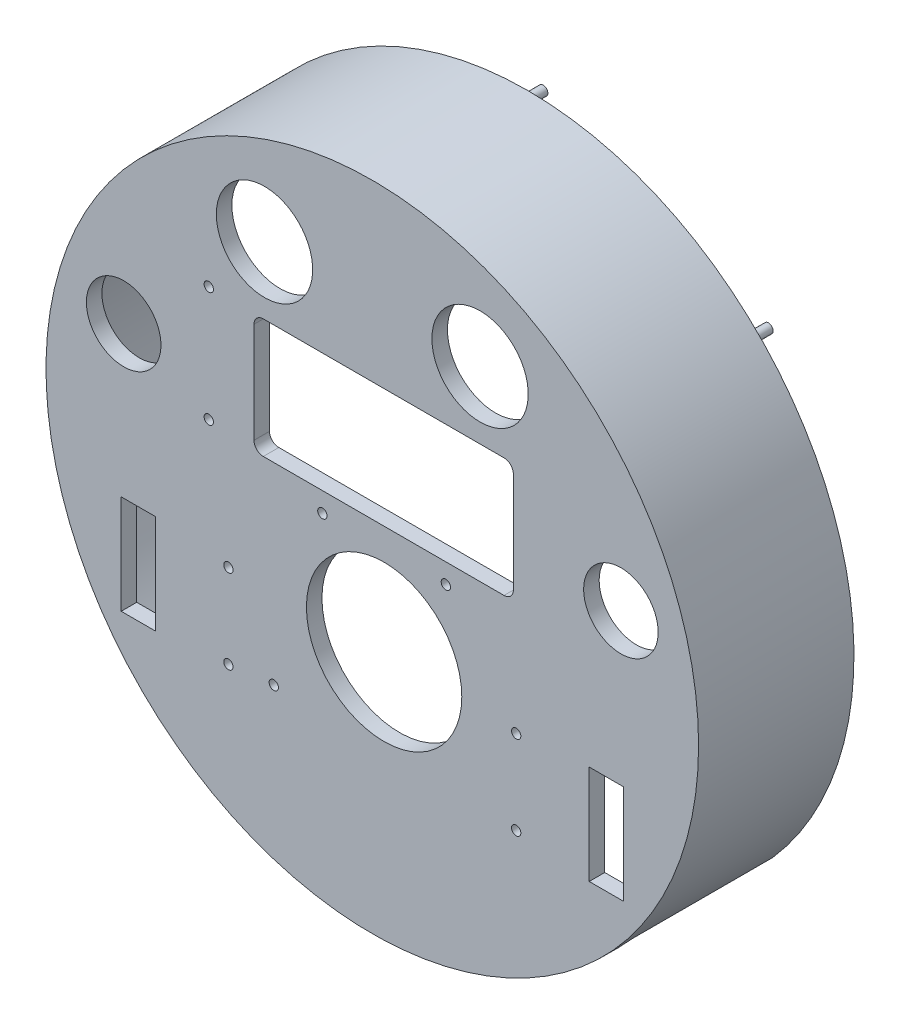
SolidWorks part; units mm, degrees
ref_plane "Plan de face" through (0, 0, 0) normal (0, 0, 1) x (1, 0, 0)
ref_plane "Plan de dessus" through (0, 0, 0) normal (0, 1, 0) x (1, 0, 0)
ref_plane "Plan de droite" through (0, 0, 0) normal (1, 0, 0) x (0, 0, -1)
sketch "Esquisse1" plane through (0, 0, 0) normal (0, 0, 1) x (1, 0, 0)
  circle A0 centre (0, 0) radius 105
  dimension "D1" = 210
extrude "Boss.-Extru.1" add sketch "Esquisse1" along normal blind 50
shell "Coque1" thickness 5
sketch3d "Esquisse3D1"
  line L0 (0, 0, 0) -> (0, 0, 42.8411) construction
  line L1 (0, -105, 0) -> (0, -105, 50) construction
  circle A3 centre (0, 0, 0) radius 105 construction
  circle A4 centre (0, 0, 50) radius 105 construction
  point P9 (0, 0, 105)
  point P12 (0, 0, 155)
sketch "Esquisse3" plane through (0, 0, 45) normal (0, 0, -1) x (-1, 0, 0)
  circle A0 centre (-3.8, -24.5576) radius 25
  circle A1 centre (-23.6695, 4.1345) radius 1.5
  circle A2 centre (16.0695, 4.1345) radius 1.5
  circle A3 centre (31.7, -51.5576) radius 1.5
extrude "Enlèv. mat.-Extru.1" cut sketch "Esquisse3" against normal blind 10
sketch "Esquisse5" plane through (0, 0, 45) normal (0, 0, -1) x (-1, 0, 0)
  line L1 (-42.3889, 10.4726) -> (35.0744, 10.4726)
  line L2 (-45.3889, 13.4726) -> (-45.3889, 45.8069)
  line L3 (-42.3889, 48.8069) -> (35.0744, 48.8069)
  line L4 (38.0744, 13.4726) -> (38.0744, 45.8069)
  arc A0 (35.0744, 48.8069) -> (38.0744, 45.8069) centre (35.0744, 45.8069) cw
  arc A1 (35.0744, 10.4726) -> (38.0744, 13.4726) centre (35.0744, 13.4726) ccw
  arc A2 (-42.3889, 10.4726) -> (-45.3889, 13.4726) centre (-42.3889, 13.4726) cw
  arc A3 (-45.3889, 45.8069) -> (-42.3889, 48.8069) centre (-42.3889, 45.8069) cw
  dimension "D1" = 3
extrude "Enlèv. mat.-Extru.2" cut sketch "Esquisse5" against normal through all
sketch "Esquisse6" plane through (0, 0, 0) normal (0, 0, -1) x (-1, 0, 0)
  line L0 (-78.8107, -69.3821) -> (78.8107, -69.3821)
  line L1 (78.5009, -69.3821) -> (-78.8107, -69.3821) construction
  circle A0 centre (0, 0) radius 105 construction
  arc A1 (-78.8107, -69.3821) -> (78.8107, -69.3821) centre (0, 0) ccw
extrude "Enlèv. mat.-Extru.3" cut sketch "Esquisse6" against normal blind 45
sketch "Esquisse7" plane through (0, 0, 45) normal (0, 0, -1) x (-1, 0, 0)
  circle A0 centre (52.6142, 48.9901) radius 1.5
  circle A1 centre (52.6142, 11.9901) radius 1.5
  circle A2 centre (46.3, -26.0576) radius 1.5
  circle A3 centre (46.3, -53.0576) radius 1.5
  circle A4 centre (-46.3, -26.0622) radius 1.5
  circle A5 centre (-46.3, -53.0622) radius 1.5
extrude "Enlèv. mat.-Extru.4" cut sketch "Esquisse7" against normal through all
sketch "Esquisse8" plane through (0, 0, 45) normal (0, 0, -1) x (-1, 0, 0)
  line L0 (0, 116.3573) -> (0, -138.2334) construction
  line L7 (-80.8, -55.5371) -> (-80.8, -23.6417)
  line L8 (-80.8, -23.6417) -> (-69.8, -23.6417)
  line L9 (-69.8, -55.5371) -> (-69.8, -23.6417)
  line L10 (-80.8, -55.5371) -> (-69.8, -55.5371)
  line L11 (80.8, -55.5371) -> (69.8, -55.5371)
  line L12 (69.8, -55.5371) -> (69.8, -23.6417)
  line L13 (80.8, -23.6417) -> (69.8, -23.6417)
  line L14 (80.8, -55.5371) -> (80.8, -23.6417)
extrude "Enlèv. mat.-Extru.5" cut sketch "Esquisse8" against normal blind 5
sketch "Esquisse9" plane through (0, 0, 45) normal (0, 0, -1) x (-1, 0, 0)
  circle A2 centre (34.6819, 70.4401) radius 15.5
  circle A3 centre (-34.6819, 70.4401) radius 15.5
extrude "Enlèv. mat.-Extru.7" cut sketch "Esquisse9" against normal through all
sketch "Esquisse10" plane through (-9.6819, 0.4401, 22) normal (0, 0, -1) x (-1, 0, 0)
  line L1 (-43.2214, 88.9656) -> (-42.9259, 93.8724)
  line L2 (-41.7241, 88.8754) -> (-44.7187, 89.0558) construction
  arc A0 (62.3329, -69.8221) -> (-81.6967, -69.8221) centre (-9.6819, -0.4401) ccw construction
sweep "Balayage1" add path "Esquisse10" circular profile diameter 3 parameters "D3"=3
sketch "Esquisse19" plane through (-5.54, 91.9764, 0) normal (-0.0601, 0.9982, 0) x (0.9982, 0.0601, 0)
  line L1 (38.8542, -23.5) -> (38.8542, -20.5)
  line L2 (38.8542, -23.5) -> (38.8542, -20.5)
  arc A1 (38.8542, -20.5) -> (38.8542, -23.5) centre (38.8542, -22) ccw
  arc A2 (38.8542, -20.5) -> (38.8542, -23.5) centre (38.8542, -22) ccw
  dimension "D1" = 0
extrude "Boss.-Extru.2" add sketch "Esquisse19" along normal blind 1
sketch "Esquisse20" plane through (-9.6819, 0.4401, 22) normal (0, 0, -1) x (-1, 0, 0)
  line L0 (-73.3113, 71.7436) -> (-78.4695, 72.1427)
  line L1 (-73.2211, 73.2409) -> (-73.4015, 70.2463) construction
  arc A0 (62.3329, -69.8221) -> (-81.6967, -69.8221) centre (-9.6819, -0.4401) ccw construction
sweep "Balayage2" add path "Esquisse20" circular profile diameter 3 parameters "D3"=3
sketch "Esquisse27" plane through (73.961, 5.7229, 0) normal (0.997, 0.0771, 0) x (0, 0, -1)
  line L1 (-20.5, 67.0598) -> (-23.5, 67.0598)
  line L2 (-20.5, 67.0598) -> (-23.5, 67.0598)
  arc A1 (-23.5, 67.0598) -> (-20.5, 67.0598) centre (-22, 67.0598) ccw
  arc A2 (-23.5, 67.0598) -> (-20.5, 67.0598) centre (-22, 67.0598) ccw
  dimension "D1" = 0
extrude "Boss.-Extru.3" add sketch "Esquisse27" along normal blind 2
mirror "Symétrie1" about plane through (0, 0, 0) normal (1, 0, 0) of "Balayage1", "Boss.-Extru.2", "Balayage2", "Boss.-Extru.3"
sketch "Esquisse30" plane through (0, 0, 0) normal (0, 0, -1) x (-1, 0, 0)
  line L2 (0, 145.1425) -> (0, 39.277) construction
  line L3 (0, 0) -> (-72.4784, 72.4784) construction
  line L4 (-78.8107, -69.3821) -> (-72.0148, -69.3821)
  line L5 (72.0148, -69.3821) -> (78.8107, -69.3821)
  line L6 (-78.8107, -69.3821) -> (-72.0148, -69.3821)
  line L7 (72.0148, -69.3821) -> (78.8107, -69.3821)
  arc A4 (78.8107, -69.3821) -> (-78.8107, -69.3821) centre (0, 0) ccw
  arc A5 (72.0148, -69.3821) -> (-72.0148, -69.3821) centre (0, 0) ccw
  circle A10 centre (0, 102.5) radius 1.5
  arc A11 (73.8152, -71.1166) -> (-73.8152, -71.1166) centre (0, 0) ccw
  arc A12 (73.8152, -71.1166) -> (-73.8152, -71.1166) centre (0, 0) ccw
  circle A13 centre (-72.4784, 72.4784) radius 1.5
  circle A14 centre (72.4784, 72.4784) radius 1.5
  dimension "D3" = 3
  dimension "D5" = 3
  dimension "D4" = 45
  dimension "D1" = 0
  dimension "D2" = 2.5
extrude "Boss.-Extru.4" add sketch "Esquisse30" along normal blind 5
sketch "Esquisse31" plane through (0, 0, 45) normal (0, 0, -1) x (-1, 0, 0)
  circle A0 centre (-80, 25) radius 12
  circle A1 centre (80, 25) radius 12
extrude "Enlèv. mat.-Extru.8" cut sketch "Esquisse31" against normal blind 5
